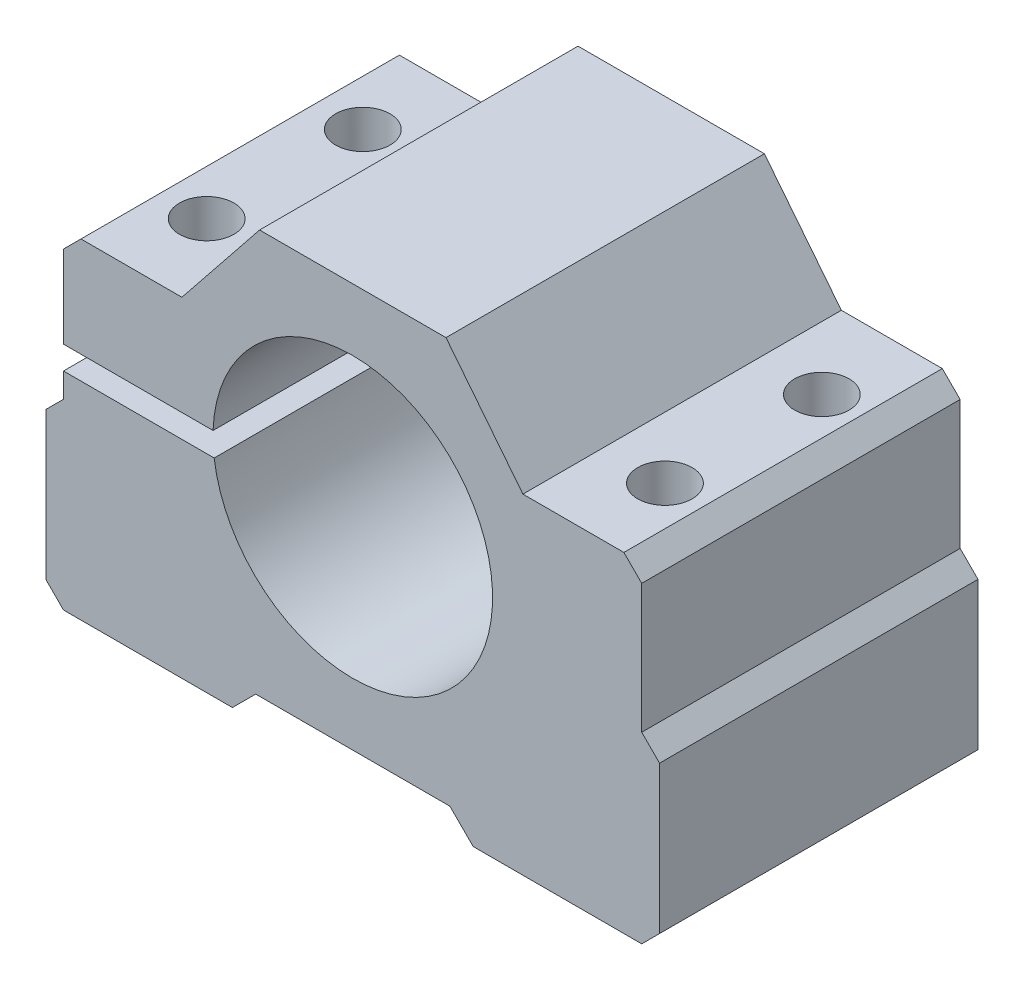
SolidWorks part; units mm, degrees
ref_plane "Front Plane" through (0, 0, 0) normal (0, 0, 1) x (1, 0, 0)
ref_plane "Top Plane" through (0, 0, 0) normal (0, 1, 0) x (1, 0, 0)
ref_plane "Right Plane" through (0, 0, 0) normal (1, 0, 0) x (0, 0, -1)
sketch "草图1" plane through (0, 0, 0) normal (0, 0, 1) x (1, 0, 0)
  line L69 (39.5, 0) -> (39.5, 3)
  line L74 (27, 3) -> (52, 3)
  line L75 (79, 2.2971) -> (79, 21.2971)
  line L76 (55, 0) -> (76.7029, 0)
  line L77 (39.5, 0) -> (39.5, 29) construction
  line L78 (2.2502, 40.2498) -> (2.2502, 29.6467)
  line L79 (2.2502, 29.6467) -> (21.5116, 29.6467)
  line L80 (27.5, 55) -> (51.5, 55)
  line L81 (39.5, 55) -> (39.5, 42.5) construction
  line L83 (27.5, 55) -> (27.5, 42.4164) construction
  line L84 (51.5, 55) -> (51.4059, 42.5) construction
  line L85 (17.5003, 42.5) -> (4.5003, 42.5)
  line L86 (27.5, 55) -> (17.5003, 42.5)
  line L87 (61.4059, 42.5) -> (74.4059, 42.5)
  line L88 (51.5, 55) -> (61.4059, 42.5)
  line L93 (2.2502, 42.5) -> (2.2502, 29.6467) construction
  line L96 (76.7029, 42.5) -> (76.7029, 50.5982) construction
  line L97 (4.5003, 42.5) -> (2.2502, 40.2498)
  line L98 (74.4059, 42.5) -> (76.7029, 40.2029)
  line L99 (2.2502, 0) -> (0, 2.2502)
  line L100 (76.7029, 0) -> (79, 2.2971)
  line L101 (79, 21.2971) -> (76.7029, 23.5941)
  line L102 (76.7029, 23.5941) -> (76.7029, 40.2029)
  line L103 (0, 2.2502) -> (0, 21.2502)
  line L104 (0, 21.2502) -> (2.2502, 23.5003)
  line L105 (2.2502, 23.5003) -> (2.2502, 26.6523)
  line L106 (2.2502, 0) -> (24, 0)
  line L107 (24, 0) -> (27, 3)
  line L108 (55, 0) -> (52, 3)
  line L109 (2.2502, 26.6523) -> (2.2502, -977.6439) construction
  line L110 (21.6538, 26.6523) -> (2.2502, 26.6523)
  line L111 (2.2502, 29.6467) -> (2.2502, 40.2498)
  arc A0 (21.6538, 26.6523) -> (21.5116, 29.6467) centre (39.5, 29) ccw
  point P0 (21.6538, 26.6523)
  point P8 (39.5, 3)
  point P19 (39.5, 55)
  point P24 (39.5, 42.5)
  dimension "D3" = 36
  dimension "D4" = 24
  dimension "D6" = 12.5
extrude "凸台-拉伸5" add sketch "草图1" along normal blind 41 contours A0 L110 L105 L104 L103 L99 L106 L107 L74 L108 L76 L100 L75 L101 L102 L98 L87 L88 L80 L86 L85 L97 L78 L79
sketch "草图2" plane through (0, 0, 0) normal (0, -1, 0) x (-1, 0, 0)
  line L0 (0, -41) -> (0, 0) construction
  line L1 (0, 0) -> (-79, 0) construction
  line L2 (0, 0) -> (0, -41) construction
  line L3 (0, -41) -> (-79, -41) construction
  line L4 (-79, 0) -> (-79, -41) construction
  line L5 (0, -20.5) -> (-92.0589, -20.5) construction
  line L6 (-40.0163, 7.4151) -> (-40.0163, -48.4151) construction
  line L7 (-10.4353, -10.6424) -> (-10.332, -30.6424) construction
  line L8 (-10.332, -30.6424) -> (-69.332, -30.6424) construction
  line L9 (-69.332, -30.6424) -> (-69.5385, -10.6424) construction
  line L10 (-69.5385, -10.6424) -> (-10.4353, -10.6424) construction
  circle A3 centre (-10.4353, -10.6424) radius 3.5
  circle A4 centre (-10.332, -30.6424) radius 3.5
  circle A5 centre (-69.332, -30.6424) radius 3.5
  circle A6 centre (-69.5385, -10.6424) radius 3.5
  point P19 (-40.0163, -20.5)
  dimension "D1" = 20
  dimension "D2" = 20
  dimension "D3" = 59
extrude "切除-拉伸3" cut sketch "草图2" against normal blind 50
